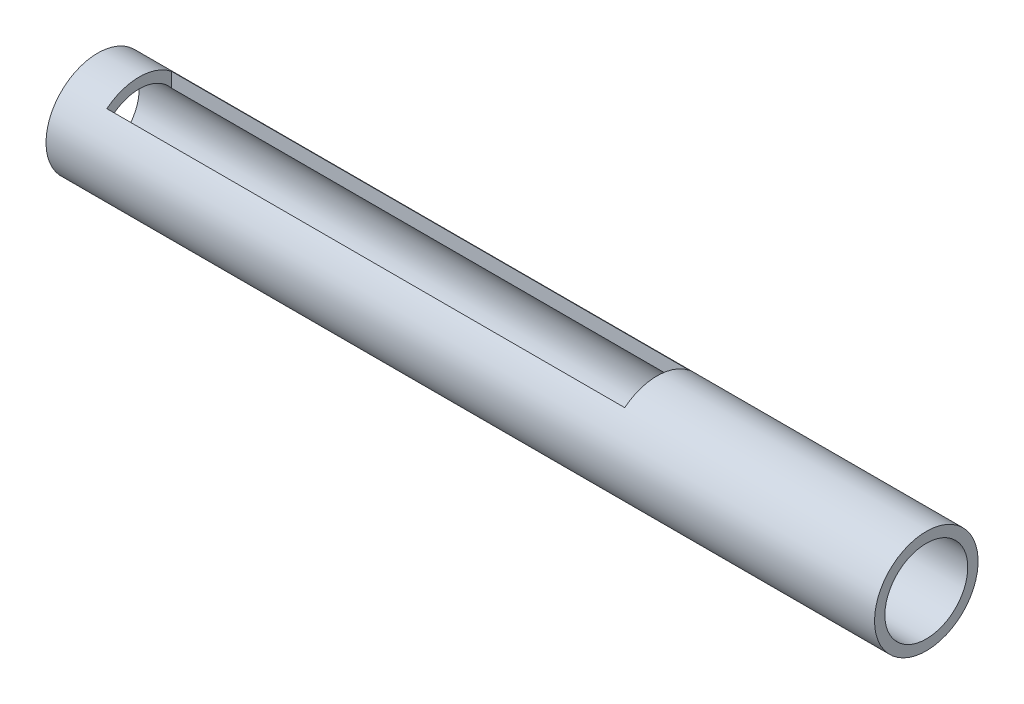
SolidWorks part; units mm, degrees
ref_plane "Front Plane" through (0, 0, 0) normal (0, 0, 1) x (1, 0, 0)
ref_plane "Top Plane" through (0, 0, 0) normal (0, 1, 0) x (1, 0, 0)
ref_plane "Right Plane" through (0, 0, 0) normal (1, 0, 0) x (0, 0, -1)
sketch "Sketch3" plane through (0, 0, 0) normal (0, 0, 1) x (1, 0, 0)
  line L0 (-172.0736, 37.709) -> (-172.0736, 12.709)
  line L2 (227.9264, 12.709) -> (227.9264, 37.709)
  line L3 (227.9264, 37.709) -> (-172.0736, 37.709)
  line L4 (-172.0736, 12.709) -> (227.9264, 12.709)
  dimension "D2" = 25
  dimension "D3" = 400
revolve "Revolve1" add sketch "Sketch3" angle 360 about L4
ref_point "Point1"
sketch "Sketch5" plane through (-172.0736, 0, 0) normal (-1, 0, 0) x (0, 0, 1)
  circle A0 centre (0, 12.709) radius 20
  dimension "D1" = 40
ref_plane "Plane1" through (0, 100, 0) normal (0, 1, 0) x (1, 0, 0)
extrude "Cut-Extrude3" cut sketch "Sketch5" against normal through all contours A0
sketch "Sketch8" plane through (0, 100, 0) normal (0, 1, 0) x (1, 0, 0)
  line L0 (-152.0736, 15.6185) -> (-152.0736, -15.6185)
  line L1 (-172.0736, 25) -> (-172.0736, -25) construction
  line L7 (-152.0736, -15.6185) -> (97.9264, -15.6185)
  line L8 (97.9264, -15.6185) -> (97.9264, 15.6185)
  line L9 (97.9264, 15.6185) -> (-152.0736, 15.6185)
  dimension "D1" = 250
  dimension "D2" = 20
extrude "Cut-Extrude2" cut sketch "Sketch8" against normal blind 78
equation "\"Big_base_height\" = 5cm"
equation "\"small_base_height\"= 5cm"
equation "\"length_base\"= 40cm"
equation "\"D1@Sketch3\"=\"Big_base_height\"*0.5"
equation "\"D2@Sketch3\"=\"small_base_height\"*0.5"
equation "\"D1@Sketch5\"= \"Big_base_height\" * 0.8"
equation "\"draft\"= atn ( \"length_base\" / ( 0.5 * 0.8 * \"Big_base_height\" ) ) * 1deg"
equation "\"D3@Sketch3\"=\"length_base\""
equation "\"length_ext\" = \"target_ext\" - \"hub_radius\" - \"length_base\""
equation "\"D1@Sketch8\"=\"length_ext\""
equation "\"diff_radius\"= 0.5 * ( \"Big_base_height\" * 0.8 - \"small_base_height\" * 0.8 )"
equation "\"hub_radius\"= 10cm"
equation "\"target_ext\"= 75cm"
equation "\"D2@Sketch8\"= \"length_base\" * 0.05"
equation "\"draft_angle\"= IIF ( ( atn ( \"diff_radius\" / \"length_base\" ) * 1deg ) < 0.5deg , 0deg , atn ( \"diff_radius\" / \"length_base\" ) * 1deg )"
equation "\"D3@Cut-Extrude3\"=\"draft_angle\""
